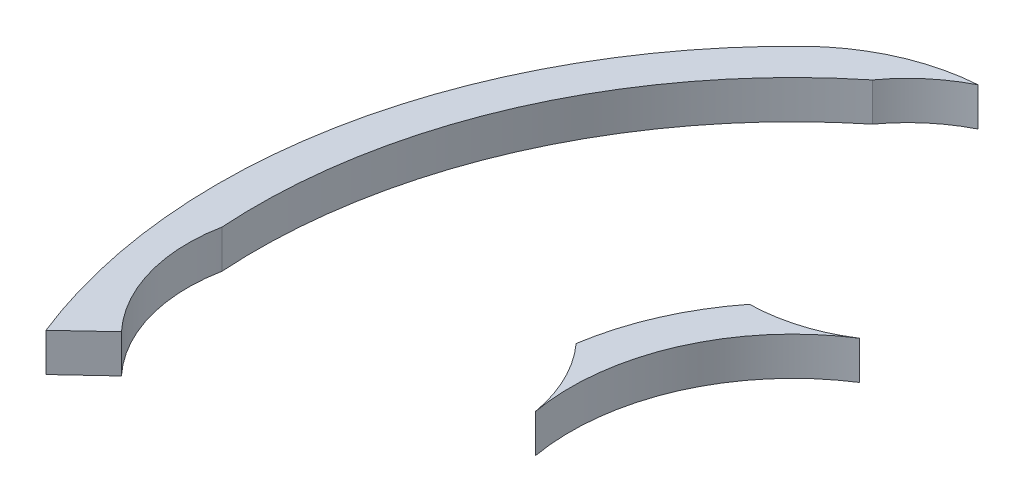
SolidWorks part; units mm, degrees
ref_plane "Plan de face" through (0, 0, 0) normal (0, 0, 1) x (1, 0, 0)
ref_plane "Plan de dessus" through (0, 0, 0) normal (0, 1, 0) x (1, 0, 0)
ref_plane "Plan de droite" through (0, 0, 0) normal (1, 0, 0) x (0, 0, -1)
sketch "Esquisse1" plane through (0, 0, 0) normal (0, 1, 0) x (1, 0, 0)
  line L0 (-85.9864, -39.221) -> (-80.901, -34.4645)
  line L3 (-9.4508, 5.6286) -> (-14.9085, -3.5351) construction
  line L5 (3.3105, -15.9387) -> (9.4508, -5.6286) construction
  line L12 (0, 0) -> (-80, 0) construction
  line L13 (-64.4502, -24.994) -> (-51.2217, 24.3754) construction
  line L14 (-65, 0) -> (-64.4502, -24.994) construction
  arc A0 (-44.8834, -16.4709) -> (3.3105, -15.9387) centre (-21.2415, 25) ccw construction
  arc A1 (-19.868, -3.8238) -> (-14.9085, -3.5351) centre (-17.486, -2) ccw construction
  arc A2 (-19.868, -3.8238) -> (-32.0272, 12.9486) centre (294.4534, 236.8392) cw construction
  arc A3 (-13.5326, 17.4331) -> (-23.8264, -39.4451) centre (-16.3245, -11.4322) ccw
  arc A4 (-43.0332, 9.6068) -> (-49.9076, -6.124) centre (-16.3245, -11.4322) ccw
  arc A5 (-13.0513, 22.4098) -> (-25.1198, -44.2749) centre (-16.3245, -11.4322) ccw construction
  arc A6 (-60.3658, 42.977) -> (-86.1705, -16.0732) centre (-16.3245, -11.4322) ccw
  arc A36 (-51.2217, 24.3754) -> (-64.4502, -24.994) centre (-16.3245, -11.4322) ccw construction
  arc A37 (-68.6703, 42.2792) -> (-85.9864, -39.221) centre (-16.3245, -11.4322) ccw
  arc A41 (9.4508, -5.6286) -> (-9.4508, 5.6286) centre (0, 0) ccw construction
  arc A42 (-16.402, 38.5677) -> (-47.4539, -50.5598) centre (-16.3245, -11.4322) ccw construction
  arc A43 (-52.9274, 49.3171) -> (-32.0272, 12.9486) centre (-43.3981, 30.6037) ccw
  arc A44 (-52.9274, 49.3171) -> (-68.6703, 42.2792) centre (-51.2217, 24.3754) ccw
  arc A45 (-44.8834, -16.4709) -> (-80.901, -34.4645) centre (-65.564, -20.1196) ccw
  point P78 (-56.6847, 2.6915)
  point P85 (-65, 0)
  dimension "D4" = 25
  dimension "D5" = 12
  dimension "D6" = 21
  dimension "D7" = 5
  dimension "D8" = 25
  dimension "D9" = 5
  dimension "D10" = 3
  dimension "D11" = 17.6
  dimension "D18" = 80
  dimension "D20" = 75
  dimension "D26" = 11
  dimension "D13" = 50
  dimension "D14" = 21
  dimension "D12" = 2
  dimension "D22" = 25
  dimension "D23" = 75
  dimension "D24" = 28
  dimension "D25" = 15
  dimension "D30" = 10
  dimension "D32" = 5
extrude "Boss.-Extru.1" add sketch "Esquisse1" along normal blind 5 contours A45 A3 A43 A44 A37 L0 | A45 A3 A43 A4
